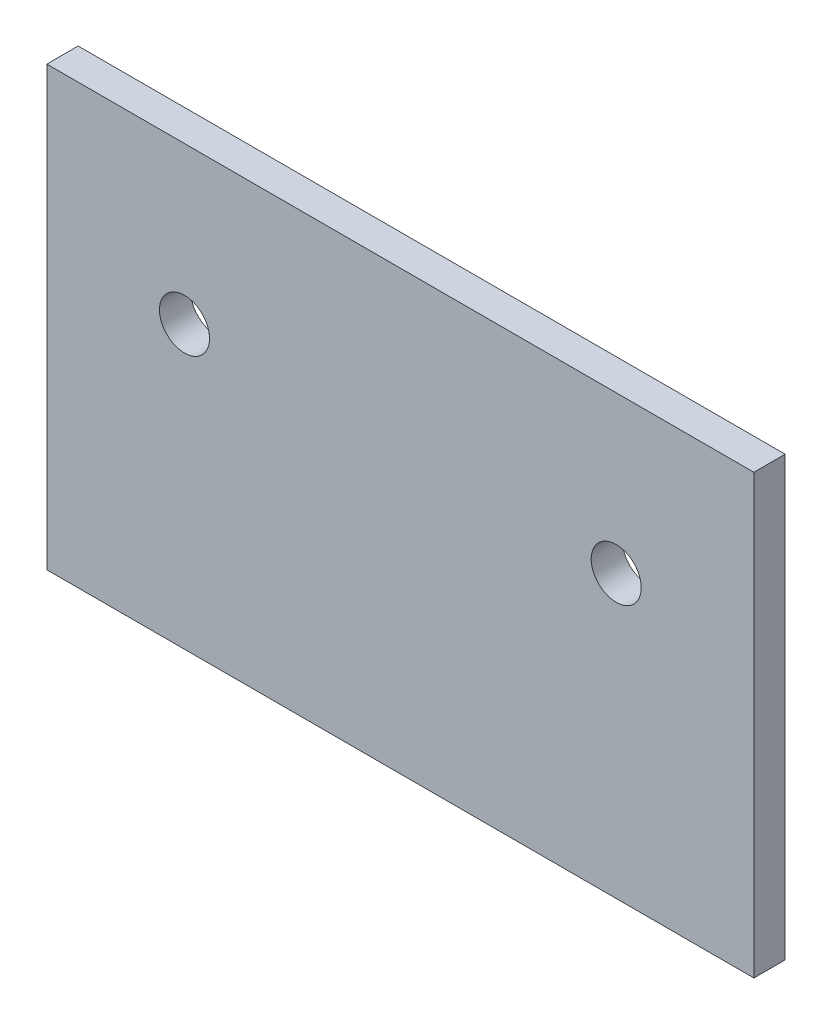
SolidWorks part; units mm, degrees
ref_plane "前视基准面" through (0, 0, 0) normal (0, 0, 1) x (1, 0, 0)
ref_plane "上视基准面" through (0, 0, 0) normal (0, 1, 0) x (1, 0, 0)
ref_plane "右视基准面" through (0, 0, 0) normal (1, 0, 0) x (0, 0, -1)
sketch "草图1" plane through (0, 0, 0) normal (0, 0, 1) x (1, 0, 0)
  line L1 (56.5, -35) -> (-56.5, -35)
  line L2 (56.5, -35) -> (56.5, 35)
  line L3 (56.5, 35) -> (-56.5, 35)
  line L4 (-56.5, -35) -> (-56.5, 35)
  line L5 (56.5, -35) -> (-56.5, 35) construction
  line L6 (56.5, 35) -> (-56.5, -35) construction
  circle A0 centre (-34.5, 10) radius 4
  circle A1 centre (34.5, 10) radius 4
  point P0 (0, 0)
  point P6 (-34.5, 10)
  point P9 (34.5, 10)
  dimension "D5" = 22
  dimension "D1" = 113
  dimension "D2" = 70
  dimension "D3" = 25
  dimension "D4" = 22
  dimension "D6" = 25
extrude "凸台-拉伸1" add sketch "草图1" along normal blind 5
